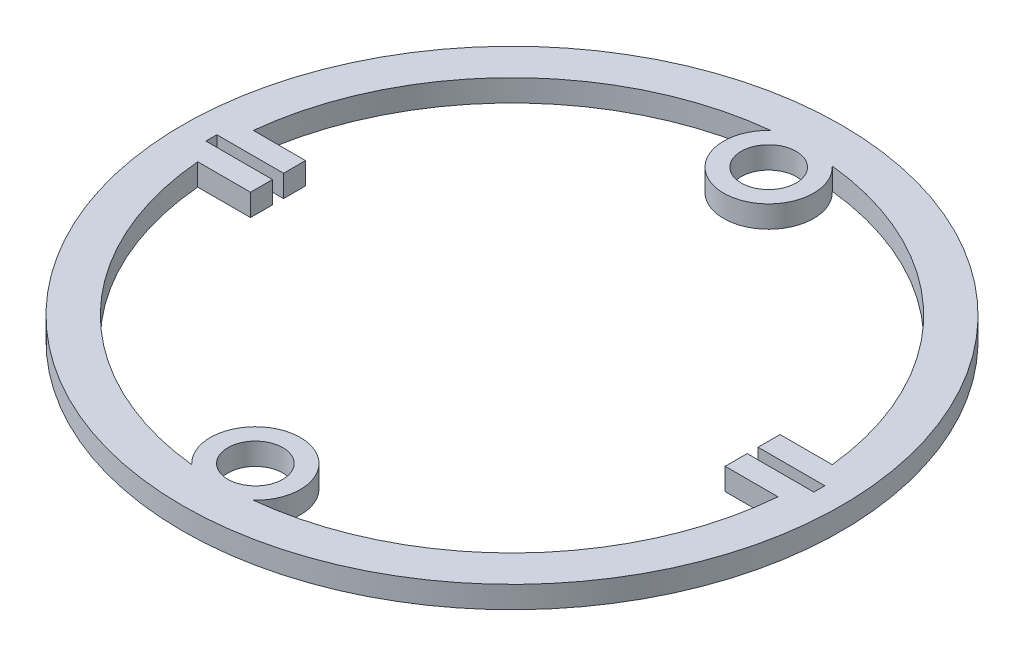
SolidWorks part; units mm, degrees
ref_plane "Front Plane" through (0, 0, 0) normal (0, 0, 1) x (1, 0, 0)
ref_plane "Top Plane" through (0, 0, 0) normal (0, 1, 0) x (1, 0, 0)
ref_plane "Right Plane" through (0, 0, 0) normal (1, 0, 0) x (0, 0, -1)
sketch "Sketch1" plane through (0, 0, 0) normal (0, 1, 0) x (1, 0, 0)
  line L0 (-35.144, 1.0185) -> (-35.144, -0.2515)
  line L5 (-35.144, 1.0185) -> (-27.4289, 1.0185)
  line L7 (35.144, 1.0185) -> (35.144, -0.2515)
  line L8 (-27.4289, 1.0185) -> (-27.4289, 3.5585)
  line L9 (-27.4289, 3.5585) -> (-33.4663, 3.5585)
  line L10 (-35.144, -0.2515) -> (-27.4371, -0.2515)
  line L11 (-27.4371, -0.2515) -> (-27.4371, -2.7915)
  line L12 (-27.4371, -2.7915) -> (-33.539, -2.7915)
  line L13 (0, -2.2231) -> (0, 2.2231) construction
  line L14 (27.4371, -2.7915) -> (33.539, -2.7915)
  line L15 (27.4371, -0.2515) -> (27.4371, -2.7915)
  line L16 (35.144, -0.2515) -> (27.4371, -0.2515)
  line L17 (35.144, 1.0185) -> (27.4289, 1.0185)
  line L18 (27.4289, 1.0185) -> (27.4289, 3.5585)
  line L19 (27.4289, 3.5585) -> (33.4663, 3.5585)
  circle A0 centre (0, 0) radius 38.1
  arc A3 (-33.539, -2.7915) -> (33.539, -2.7915) centre (0, 0) ccw construction
  arc A4 (-33.539, -2.7915) -> (33.539, -2.7915) centre (0, 0) ccw
  arc A5 (33.4663, 3.5585) -> (-33.4663, 3.5585) centre (0, 0) ccw construction
  arc A6 (33.4663, 3.5585) -> (-33.4663, 3.5585) centre (0, 0) ccw
  point P4 (-35.144, 0.3835)
  point P18 (0, 0)
  dimension "D1" = 76.2
  dimension "D3" = 35.144
  dimension "D4" = 35.144
  dimension "D5" = 1.27
  dimension "D6" = 2.54
  dimension "D7" = 2.54
  dimension "D8" = 1.27
extrude "Boss-Extrude1" add sketch "Sketch1" along normal blind 50.8
sketch "Sketch4" plane through (0, 50.8, 0) normal (0, 1, 0) x (1, 0, 0)
  line L1 (33.4663, 3.5585) -> (-33.4663, 3.5585)
  line L2 (-27.4289, 1.0185) -> (27.4289, 1.0185)
  line L3 (27.4289, 1.0185) -> (27.4371, -0.2515) construction
  line L4 (-27.4289, 1.0185) -> (-27.4371, -0.2515) construction
  line L5 (-27.4289, 1.0185) -> (-27.433, 0.3835)
  line L6 (-27.433, 0.3835) -> (-33.6528, 0.3835)
  line L7 (27.4289, 1.0185) -> (27.433, 0.3835)
  line L8 (27.433, 0.3835) -> (33.6528, 0.3835)
  circle A2 centre (0, 0) radius 38.1
  arc A5 (33.4663, 3.5585) -> (-33.4663, 3.5585) centre (0, 0) ccw
  arc A6 (-33.6528, 0.3835) -> (33.6528, 0.3835) centre (0, 0) ccw
extrude "Boss-Extrude2" add sketch "Sketch4" along normal blind 50.8
sketch "Sketch5" plane through (0, 0, 0) normal (0, -1, 0) x (1, 0, 0)
  line L0 (-3.4506, 0) -> (3.4506, 0) construction
  circle A0 centre (0, -29.6706) radius 3.175
  circle A1 centre (0, -29.6706) radius 5.207
  circle A2 centre (0, 29.6706) radius 3.175
  circle A3 centre (0, 29.6706) radius 5.207
  point P6 (0, 0)
  dimension "D1" = 6.35
  dimension "D2" = 2.032
extrude "Boss-Extrude3" add sketch "Sketch5" against normal blind 101.6
sketch "Sketch7" plane through (0, 101.6, 0) normal (0, 1, 0) x (1, 0, 0)
  circle A1 centre (0, 0) radius 38.1
  circle A2 centre (0, 0) radius 38.1
  dimension "D1" = 0
extrude "Cut-Extrude1" cut sketch "Sketch7" against normal blind 99.06
